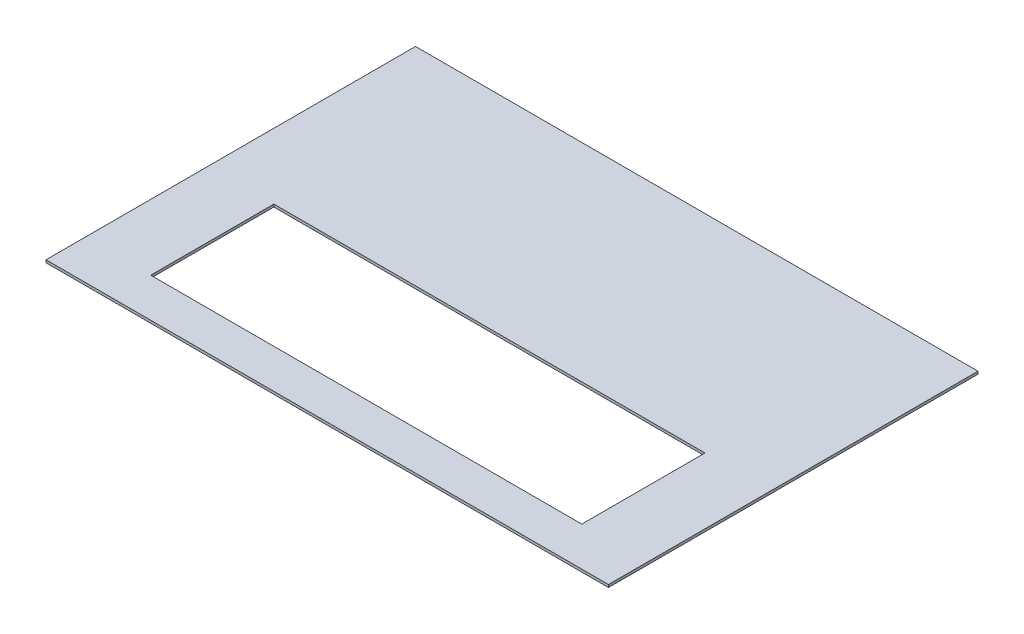
SolidWorks part; units mm, degrees
ref_plane "Front Plane" through (0, 0, 0) normal (0, 0, 1) x (1, 0, 0)
ref_plane "Top Plane" through (0, 0, 0) normal (0, 1, 0) x (1, 0, 0)
ref_plane "Right Plane" through (0, 0, 0) normal (1, 0, 0) x (0, 0, -1)
sketch "Sketch1" plane through (0, 0, 0) normal (0, 1, 0) x (1, 0, 0)
  line L1 (0, 0) -> (1370, 0)
  line L2 (0, 0) -> (0, 900)
  line L3 (0, 900) -> (1370, 900)
  line L4 (1370, 0) -> (1370, 900)
  dimension "D1" = 1370
  dimension "D2" = 900
extrude "Boss-Extrude1" add sketch "Sketch1" along normal blind 6.35
sketch "Sketch2" plane through (0, 6.35, 0) normal (0, 1, 0) x (1, 0, 0)
  line L0 (0, 0) -> (1370, 0) construction
  line L1 (160, 95) -> (1210, 95)
  line L2 (160, 95) -> (160, 395)
  line L3 (160, 395) -> (1210, 395)
  line L4 (1210, 95) -> (1210, 395)
  line L5 (0, 900) -> (0, 0) construction
  point P4 (685, 95)
  point P7 (685, 0)
  dimension "D1" = 160
  dimension "D2" = 95
  dimension "D3" = 300
extrude "Cut-Extrude1" cut sketch "Sketch2" against normal up to next
